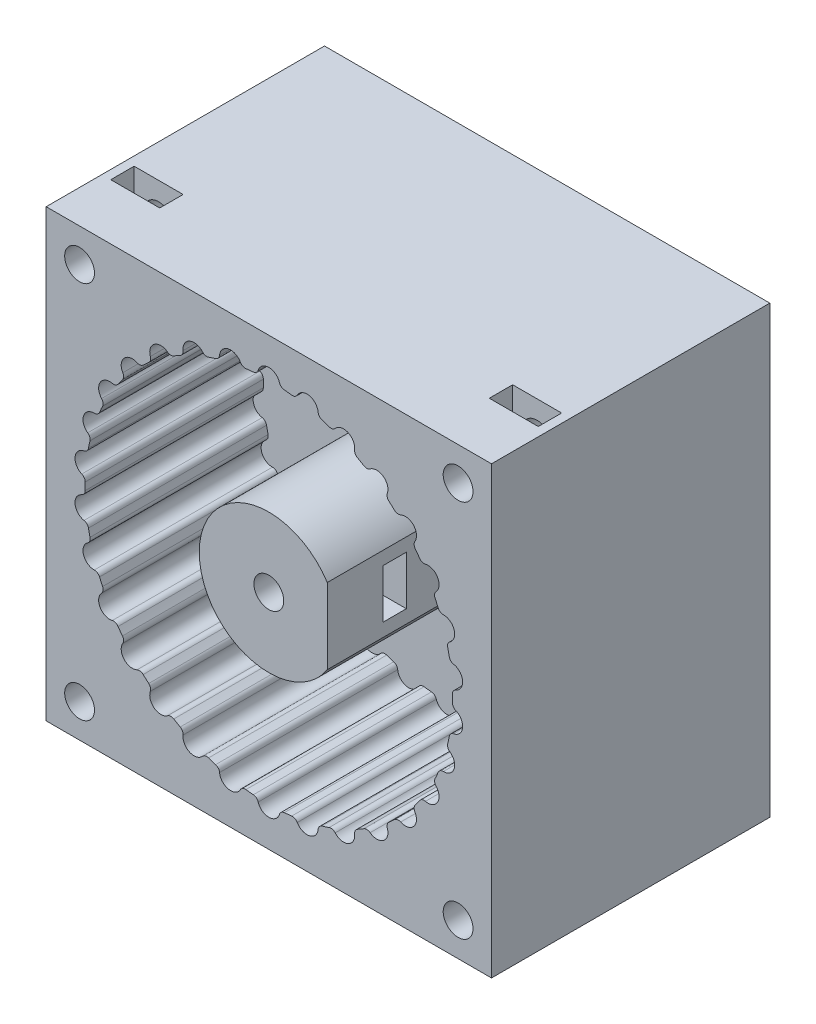
SolidWorks part; units mm, degrees
ref_plane "Front Plane" through (0, 0, 0) normal (1, 0, 0) x (0, 1, 0)
ref_plane "Top Plane" through (0, 0, 0) normal (0, 0, 1) x (0, 1, 0)
ref_plane "Right Plane" through (0, 0, 0) normal (0, 1, 0) x (-1, 0, 0)
sketch "Sketch1" plane through (0, 0, 0) normal (0, 0, 1) x (0, 1, 0)
  line L1 (25.4, -25.4) -> (-25.4, -25.4)
  line L2 (25.4, -25.4) -> (25.4, 25.4)
  line L3 (25.4, 25.4) -> (-25.4, 25.4)
  line L4 (-25.4, -25.4) -> (-25.4, 25.4)
  line L5 (25.4, -25.4) -> (-25.4, 25.4) construction
  line L6 (25.4, 25.4) -> (-25.4, -25.4) construction
  point P0 (0, 0)
  dimension "D1" = 50.8
extrude "Boss-Extrude1" add sketch "Sketch1" along normal blind 31.75
sketch "Sketch2" plane through (0, 0, 31.75) normal (0, 0, 1) x (1, 0, 0)
  line L0 (0, 20.955) -> (0, 0) construction
  line L1 (6.6675, 4.3068) -> (6.6675, -4.3068)
  circle A0 centre (0, 0) radius 7.9375
  circle A1 centre (0, 0) radius 20.955
  arc A2 (-1.2143, 21.327) -> (1.2143, 21.327) centre (0, 20.955) cw
  arc A3 (1.2143, 21.327) -> (1.7679, 20.8803) centre (1.8214, 21.513) ccw
  arc A4 (-1.2143, 21.327) -> (-1.7679, 20.8803) centre (-1.8214, 21.513) cw
  arc A5 (5.6219, 20.6085) -> (6.0705, 20.0565) centre (6.2544, 20.6642) ccw
  arc A6 (3.2464, 21.1134) -> (5.6219, 20.6085) centre (4.3568, 20.4971) cw
  arc A7 (3.2464, 21.1134) -> (2.612, 20.7916) centre (2.6912, 21.4216) cw
  arc A8 (9.7838, 18.9893) -> (10.1078, 18.356) centre (10.4141, 18.9123) ccw
  arc A9 (7.5652, 19.9771) -> (9.7838, 18.9893) centre (8.5232, 19.1433) cw
  arc A10 (7.5652, 19.9771) -> (6.8778, 19.7942) centre (7.0862, 20.394) cw
  arc A11 (13.5181, 16.5402) -> (13.7034, 15.8534) centre (14.1186, 16.3338) ccw
  arc A12 (11.5533, 17.9677) -> (13.5181, 16.5402) centre (12.317, 16.953) cw
  arc A13 (11.5533, 17.9677) -> (10.8429, 17.9316) centre (11.1715, 18.475) cw
  arc A14 (16.6616, 13.3682) -> (16.7, 12.6579) centre (17.2061, 13.0414) ccw
  arc A15 (15.0365, 15.173) -> (16.6616, 13.3682) centre (15.5726, 14.0216) cw
  arc A16 (15.0365, 15.173) -> (14.3342, 15.2854) centre (14.7685, 15.7486) cw
  arc A17 (19.0769, 9.6119) -> (18.9668, 8.9091) centre (19.5415, 9.1791) ccw
  arc A18 (17.8626, 11.7151) -> (19.0769, 9.6119) centre (18.1476, 10.4775) cw
  arc A19 (17.8626, 11.7151) -> (17.1989, 11.9712) centre (17.7201, 12.3339) cw
  arc A20 (20.6584, 5.4356) -> (20.4046, 4.771) centre (21.023, 4.9156) ccw
  arc A21 (19.908, 7.7453) -> (20.6584, 5.4356) centre (19.9294, 6.4755) cw
  arc A22 (19.908, 7.7453) -> (19.312, 8.1337) centre (19.8973, 8.3802) cw
  arc A23 (21.3371, 1.0216) -> (20.9507, 0.4244) centre (21.5856, 0.4373) ccw
  arc A24 (21.0833, 3.4369) -> (21.3371, 1.0216) centre (20.8402, 2.1904) cw
  arc A25 (21.0833, 3.4369) -> (20.5811, 3.9408) centre (21.2048, 4.0602) cw
  arc A26 (21.0833, -3.4369) -> (20.5811, -3.9408) centre (21.2048, -4.0602) ccw
  arc A27 (21.3371, -1.0216) -> (21.0833, -3.4369) centre (20.8402, -2.1904) cw
  arc A28 (21.3371, -1.0216) -> (20.9507, -0.4244) centre (21.5856, -0.4373) cw
  arc A29 (19.908, -7.7453) -> (19.312, -8.1337) centre (19.8973, -8.3802) ccw
  arc A30 (20.6584, -5.4356) -> (19.908, -7.7453) centre (19.9294, -6.4755) cw
  arc A31 (20.6584, -5.4356) -> (20.4046, -4.771) centre (21.023, -4.9156) cw
  arc A32 (17.8626, -11.7151) -> (17.1989, -11.9712) centre (17.7201, -12.3339) ccw
  arc A33 (19.0769, -9.6119) -> (17.8626, -11.7151) centre (18.1476, -10.4775) cw
  arc A34 (19.0769, -9.6119) -> (18.9668, -8.9091) centre (19.5415, -9.1791) cw
  arc A35 (15.0365, -15.173) -> (14.3342, -15.2854) centre (14.7685, -15.7486) ccw
  arc A36 (16.6616, -13.3682) -> (15.0365, -15.173) centre (15.5726, -14.0216) cw
  arc A37 (16.6616, -13.3682) -> (16.7, -12.6579) centre (17.2061, -13.0414) cw
  arc A38 (11.5533, -17.9677) -> (10.8429, -17.9316) centre (11.1715, -18.475) ccw
  arc A39 (13.5181, -16.5402) -> (11.5533, -17.9677) centre (12.317, -16.953) cw
  arc A40 (13.5181, -16.5402) -> (13.7034, -15.8534) centre (14.1186, -16.3338) cw
  arc A41 (7.5652, -19.9771) -> (6.8778, -19.7942) centre (7.0862, -20.394) ccw
  arc A42 (9.7838, -18.9893) -> (7.5652, -19.9771) centre (8.5232, -19.1433) cw
  arc A43 (9.7838, -18.9893) -> (10.1078, -18.356) centre (10.4141, -18.9123) cw
  arc A44 (3.2464, -21.1134) -> (2.612, -20.7916) centre (2.6912, -21.4216) ccw
  arc A45 (5.6219, -20.6085) -> (3.2464, -21.1134) centre (4.3568, -20.4971) cw
  arc A46 (5.6219, -20.6085) -> (6.0705, -20.0565) centre (6.2544, -20.6642) cw
  arc A47 (-1.2143, -21.327) -> (-1.7679, -20.8803) centre (-1.8214, -21.513) ccw
  arc A48 (1.2143, -21.327) -> (-1.2143, -21.327) centre (0, -20.955) cw
  arc A49 (1.2143, -21.327) -> (1.7679, -20.8803) centre (1.8214, -21.513) cw
  arc A50 (-5.6219, -20.6085) -> (-6.0705, -20.0565) centre (-6.2544, -20.6642) ccw
  arc A51 (-3.2464, -21.1134) -> (-5.6219, -20.6085) centre (-4.3568, -20.4971) cw
  arc A52 (-3.2464, -21.1134) -> (-2.612, -20.7916) centre (-2.6912, -21.4216) cw
  arc A53 (-9.7838, -18.9893) -> (-10.1078, -18.356) centre (-10.4141, -18.9123) ccw
  arc A54 (-7.5652, -19.9771) -> (-9.7838, -18.9893) centre (-8.5232, -19.1433) cw
  arc A55 (-7.5652, -19.9771) -> (-6.8778, -19.7942) centre (-7.0862, -20.394) cw
  arc A56 (-13.5181, -16.5402) -> (-13.7034, -15.8534) centre (-14.1186, -16.3338) ccw
  arc A57 (-11.5533, -17.9677) -> (-13.5181, -16.5402) centre (-12.317, -16.953) cw
  arc A58 (-11.5533, -17.9677) -> (-10.8429, -17.9316) centre (-11.1715, -18.475) cw
  arc A59 (-16.6616, -13.3682) -> (-16.7, -12.6579) centre (-17.2061, -13.0414) ccw
  arc A60 (-15.0365, -15.173) -> (-16.6616, -13.3682) centre (-15.5726, -14.0216) cw
  arc A61 (-15.0365, -15.173) -> (-14.3342, -15.2854) centre (-14.7685, -15.7486) cw
  arc A62 (-19.0769, -9.6119) -> (-18.9668, -8.9091) centre (-19.5415, -9.1791) ccw
  arc A63 (-17.8626, -11.7151) -> (-19.0769, -9.6119) centre (-18.1476, -10.4775) cw
  arc A64 (-17.8626, -11.7151) -> (-17.1989, -11.9712) centre (-17.7201, -12.3339) cw
  arc A65 (-20.6584, -5.4356) -> (-20.4046, -4.771) centre (-21.023, -4.9156) ccw
  arc A66 (-19.908, -7.7453) -> (-20.6584, -5.4356) centre (-19.9294, -6.4755) cw
  arc A67 (-19.908, -7.7453) -> (-19.312, -8.1337) centre (-19.8973, -8.3802) cw
  arc A68 (-21.3371, -1.0216) -> (-20.9507, -0.4244) centre (-21.5856, -0.4373) ccw
  arc A69 (-21.0833, -3.4369) -> (-21.3371, -1.0216) centre (-20.8402, -2.1904) cw
  arc A70 (-21.0833, -3.4369) -> (-20.5811, -3.9408) centre (-21.2048, -4.0602) cw
  arc A71 (-21.0833, 3.4369) -> (-20.5811, 3.9408) centre (-21.2048, 4.0602) ccw
  arc A72 (-21.3371, 1.0216) -> (-21.0833, 3.4369) centre (-20.8402, 2.1904) cw
  arc A73 (-21.3371, 1.0216) -> (-20.9507, 0.4244) centre (-21.5856, 0.4373) cw
  arc A74 (-19.908, 7.7453) -> (-19.312, 8.1337) centre (-19.8973, 8.3802) ccw
  arc A75 (-20.6584, 5.4356) -> (-19.908, 7.7453) centre (-19.9294, 6.4755) cw
  arc A76 (-20.6584, 5.4356) -> (-20.4046, 4.771) centre (-21.023, 4.9156) cw
  arc A77 (-17.8626, 11.7151) -> (-17.1989, 11.9712) centre (-17.7201, 12.3339) ccw
  arc A78 (-19.0769, 9.6119) -> (-17.8626, 11.7151) centre (-18.1476, 10.4775) cw
  arc A79 (-19.0769, 9.6119) -> (-18.9668, 8.9091) centre (-19.5415, 9.1791) cw
  arc A80 (-15.0365, 15.173) -> (-14.3342, 15.2854) centre (-14.7685, 15.7486) ccw
  arc A81 (-16.6616, 13.3682) -> (-15.0365, 15.173) centre (-15.5726, 14.0216) cw
  arc A82 (-16.6616, 13.3682) -> (-16.7, 12.6579) centre (-17.2061, 13.0414) cw
  arc A83 (-11.5533, 17.9677) -> (-10.8429, 17.9316) centre (-11.1715, 18.475) ccw
  arc A84 (-13.5181, 16.5402) -> (-11.5533, 17.9677) centre (-12.317, 16.953) cw
  arc A85 (-13.5181, 16.5402) -> (-13.7034, 15.8534) centre (-14.1186, 16.3338) cw
  arc A86 (-7.5652, 19.9771) -> (-6.8778, 19.7942) centre (-7.0862, 20.394) ccw
  arc A87 (-9.7838, 18.9893) -> (-7.5652, 19.9771) centre (-8.5232, 19.1433) cw
  arc A88 (-9.7838, 18.9893) -> (-10.1078, 18.356) centre (-10.4141, 18.9123) cw
  arc A89 (-3.2464, 21.1134) -> (-2.612, 20.7916) centre (-2.6912, 21.4216) ccw
  arc A90 (-5.6219, 20.6085) -> (-3.2464, 21.1134) centre (-4.3568, 20.4971) cw
  arc A91 (-5.6219, 20.6085) -> (-6.0705, 20.0565) centre (-6.2544, 20.6642) cw
  dimension "D1" = 41.91
  dimension "D2" = 1.27
  dimension "D3" = 0.635
  dimension "D4" = 15.875
  dimension "D5" = 6.6675
  dimension "D6" = 30
extrude "Cut-Extrude1" cut sketch "Sketch2" against normal blind 20.32
sketch "Sketch3" plane through (0, 0, 11.43) normal (0, 0, 1) x (1, 0, 0)
  line L0 (6.6675, 4.3068) -> (6.6675, -4.3068)
  arc A0 (6.6675, 4.3068) -> (6.6675, -4.3068) centre (0, 0) ccw
  dimension "D1" = 15.875
  dimension "D2" = 6.6675
extrude "Boss-Extrude2" add sketch "Sketch3" along normal blind 20.32 contours L0 A0
sketch "Sketch4" plane through (0, 0, 31.75) normal (0, 0, 1) x (1, 0, 0)
  line L1 (21.59, -21.59) -> (-21.59, -21.59)
  line L2 (21.59, -21.59) -> (21.59, 21.59)
  line L3 (21.59, 21.59) -> (-21.59, 21.59)
  line L4 (-21.59, -21.59) -> (-21.59, 21.59)
  line L5 (21.59, -21.59) -> (-21.59, 21.59) construction
  line L6 (21.59, 21.59) -> (-21.59, -21.59) construction
  point P0 (0, 0)
  point P1 (-21.59, 21.59)
  point P2 (21.59, -21.59)
  point P3 (21.59, 21.59)
  point P4 (-21.59, -21.59)
  dimension "D1" = 43.18
  dimension "D2" = 43.18
hole_wizard "M3 Clearance Hole1" positions "Sketch4" profile "Sketch5" hole size "M3" standard "ANSI Metric"
sketch "Sketch5" plane through (0, 0, 31.75) normal (1, 0, 0) x (0, -1, 0)
  line L0 (0, 0) -> (0, 26.4215)
  line L1 (0, 26.4215) -> (1.7, 25.4)
  line L2 (1.7, 25.4) -> (1.7, 0)
  line L5 (1.7, 0) -> (0, 0)
  line L10 (0, 26.4215) -> (-1.7, 25.4) construction
  line L11 (0, -6.35) -> (0, 107.95) construction
  dimension "Hole Dia." = 3.4
  dimension "Hole Depth" = 25.4
  dimension "Drill Angle" = 118
ref_plane "Plane1" through (0, 0, 25.4) normal (0, 0, 1) x (0, 1, 0)
sketch "Sketch6" plane through (0, 0, 25.4) normal (0, 0, 1) x (0, 1, 0)
  line L0 (-25.4, 25.4) -> (-25.4, -25.4) construction
  line L1 (-18.3638, 21.59) -> (-19.9769, 24.384)
  line L2 (-19.9769, 24.384) -> (-23.2031, 24.384)
  line L3 (-23.2031, 24.384) -> (-24.8162, 21.59)
  line L4 (-24.8162, 21.59) -> (-23.2031, 18.796)
  line L5 (-23.2031, 18.796) -> (-19.9769, 18.796)
  line L6 (-19.9769, 18.796) -> (-18.3638, 21.59)
  line L7 (18.3638, 21.59) -> (19.9769, 18.796)
  line L8 (19.9769, 18.796) -> (23.2031, 18.796)
  line L9 (23.2031, 18.796) -> (24.8162, 21.59)
  line L10 (24.8162, 21.59) -> (23.2031, 24.384)
  line L11 (23.2031, 24.384) -> (19.9769, 24.384)
  line L12 (19.9769, 24.384) -> (18.3638, 21.59)
  line L13 (18.3638, -21.59) -> (19.9769, -24.384)
  line L14 (19.9769, -24.384) -> (23.2031, -24.384)
  line L15 (23.2031, -24.384) -> (24.8162, -21.59)
  line L16 (24.8162, -21.59) -> (23.2031, -18.796)
  line L17 (23.2031, -18.796) -> (19.9769, -18.796)
  line L18 (19.9769, -18.796) -> (18.3638, -21.59)
  line L19 (-18.3638, -21.59) -> (-19.9769, -18.796)
  line L20 (-19.9769, -18.796) -> (-23.2031, -18.796)
  line L21 (-23.2031, -18.796) -> (-24.8162, -21.59)
  line L22 (-24.8162, -21.59) -> (-23.2031, -24.384)
  line L23 (-23.2031, -24.384) -> (-19.9769, -24.384)
  line L24 (-19.9769, -24.384) -> (-18.3638, -21.59)
  line L25 (0, 3.2262) -> (-2.794, 1.6131)
  line L26 (-2.794, 1.6131) -> (-2.794, -1.6131)
  line L27 (-2.794, -1.6131) -> (0, -3.2262)
  line L28 (0, -3.2262) -> (2.794, -1.6131)
  line L29 (2.794, -1.6131) -> (2.794, 1.6131)
  line L30 (2.794, 1.6131) -> (0, 3.2262)
  line L31 (-23.2031, -18.796) -> (-25.4, -18.796)
  line L32 (-23.2031, -18.796) -> (-23.2031, -24.384)
  line L33 (-23.2031, -24.384) -> (-25.4, -24.384)
  line L34 (-25.4, -18.796) -> (-25.4, -24.384)
  line L35 (25.4, -25.4) -> (25.4, 25.4) construction
  line L36 (23.2031, -18.796) -> (25.4, -18.796)
  line L37 (23.2031, -18.796) -> (23.2031, -24.384)
  line L38 (23.2031, -24.384) -> (25.4, -24.384)
  line L39 (25.4, -18.796) -> (25.4, -24.384)
  line L40 (4.3068, -6.6675) -> (-4.3068, -6.6675) construction
  line L41 (23.2031, 24.384) -> (25.4, 24.384)
  line L42 (23.2031, 24.384) -> (23.2031, 18.796)
  line L43 (23.2031, 18.796) -> (25.4, 18.796)
  line L44 (25.4, 24.384) -> (25.4, 18.796)
  line L45 (-23.2031, 24.384) -> (-25.4, 24.384)
  line L46 (-23.2031, 24.384) -> (-23.2031, 18.796)
  line L47 (-23.2031, 18.796) -> (-25.4, 18.796)
  line L48 (-25.4, 24.384) -> (-25.4, 18.796)
  line L49 (-2.794, -1.6131) -> (2.794, -1.6131)
  line L50 (-2.794, -1.6131) -> (-2.794, -6.6675)
  line L51 (-2.794, -6.6675) -> (2.794, -6.6675)
  line L52 (2.794, -1.6131) -> (2.794, -6.6675)
  circle A0 centre (-21.59, 21.59) radius 2.794 construction
  circle A1 centre (21.59, 21.59) radius 2.794 construction
  circle A2 centre (21.59, -21.59) radius 2.794 construction
  circle A3 centre (-21.59, -21.59) radius 2.794 construction
  circle A4 centre (0, 0) radius 2.794 construction
  dimension "D1" = 5.588
extrude "Cut-Extrude2" cut sketch "Sketch6" against normal blind 2.667 contours L44 L41 L10 L9 L43 | L42 L11 L12 L7 L8 | L37 L17 L18 L13 L14 | L39 L36 L16 L15 L38 | L31 L34 L33 L22 L21 | L20 L32 L23 L24 L19 | L32 L21 L22 | L16 L37 L15 | L10 L42 L9 | L2 L46 L5 L6 L1 | L46 L3 L4 | L45 L48 L47 L4 L3 | L26 L49 L29 L30 L25 | L49 L27 L28 | L52 L28 L27 L50 L51
equation "\"D5@Sketch2\"=0.5*0.625-0.05"
equation "\"D2@Sketch3\"=0.5*0.625-0.05"
